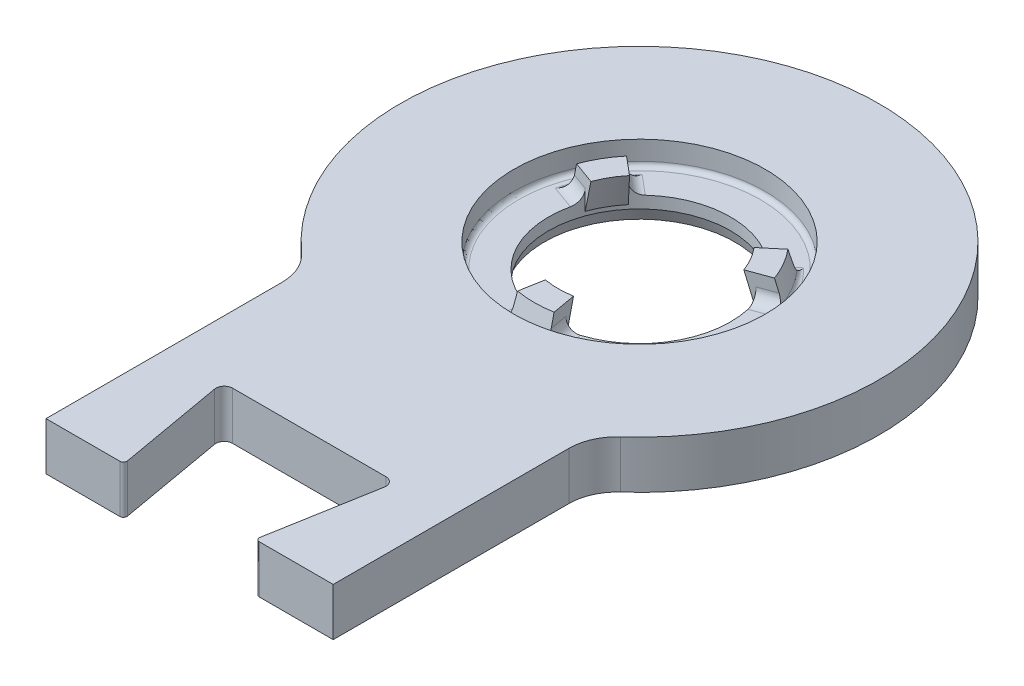
SolidWorks part; units mm, degrees
ref_plane "Front Plane" through (0, 0, 0) normal (0, 0, 1) x (1, 0, 0)
ref_plane "Top Plane" through (0, 0, 0) normal (0, 1, 0) x (1, 0, 0)
ref_plane "Right Plane" through (0, 0, 0) normal (1, 0, 0) x (0, 0, -1)
sketch "Sketch1" plane through (0, 0, 0) normal (0, 1, 0) x (1, 0, 0)
  line L0 (-6, 6) -> (-6, -13.2915)
  line L1 (-6, -19) -> (-2.7023, -19)
  line L2 (6, -19) -> (6, -13.2915)
  line L3 (6, 6) -> (-6, 6)
  line L4 (-6, -13.2915) -> (-6, -19)
  line L5 (6, -13.2915) -> (6, 6)
  line L6 (0, -19) -> (0, 0) construction
  line L7 (-2.6007, -19) -> (-3.5, -13.9) construction
  line L8 (-3.5, -13.9) -> (0, -13.9) construction
  line L9 (-2.7023, -19) -> (-3.6192, -13.8)
  line L10 (-3.6192, -13.8) -> (0, -13.8)
  line L11 (-2.6992, -19.0174) -> (-3.6192, -13.8) construction
  line L12 (2.7023, -19) -> (6, -19)
  line L13 (3.6192, -13.8) -> (0, -13.8)
  line L14 (2.7023, -19) -> (3.6192, -13.8)
  circle A0 centre (0, 0) radius 4
  dimension "D1" = 8
  dimension "D5" = 6
  dimension "D7" = 80
  dimension "D2" = 25
  dimension "D3" = 6
  dimension "D4" = 12
  dimension "D8" = 3.5
  dimension "D9" = 5.1
  dimension "D10" = 0.1
extrude "Boss-Extrude1" add sketch "Sketch1" along normal blind 2
sketch "Sketch2" plane through (0, 0, 0) normal (0, 1, 0) x (1, 0, 0)
  circle A0 centre (0, 0) radius 10
  circle A1 centre (0, 0) radius 3.8
  dimension "D1" = 20
  dimension "D2" = 7.6
extrude "Boss-Extrude2" add sketch "Sketch2" along normal blind 2
sketch "Sketch3" plane through (0, 0, 0) normal (0, -1, 0) x (1, 0, 0)
  line L0 (-3, 0) -> (-3, 4)
  line L1 (3, 0) -> (3, 4)
  arc A0 (-3, 0) -> (3, 0) centre (0, 0) ccw
  arc A1 (-3, 4) -> (3, 4) centre (0, 0) ccw
extrude "Boss-Extrude3" [suppressed] add sketch "Sketch3" along normal blind 4
fillet "Fillet1" [suppressed] radius 0.5
fillet "Fillet2" [suppressed] radius 1
sketch "Sketch4" plane through (0, 2, 0) normal (0, 1, 0) x (1, 0, 0)
  line L0 (-6, -8) -> (-6, -19) construction
  line L1 (-6, -18.8) -> (6, -18.8)
  line L2 (-6, -18.8) -> (-6, -19)
  line L3 (-6, -19) -> (6, -19)
  line L4 (6, -18.8) -> (6, -19)
  dimension "D1" = 0.2
extrude "Cut-Extrude1" cut sketch "Sketch4" against normal blind 4
fillet "Fillet3" radius 0.35 2 edges at (3.6192, 1, 13.8) (-3.6192, 1, 13.8)
fillet "Fillet4" radius 0.15 2 edges at (2.7375, 1, 18.8) (-2.7375, 1, 18.8)
sketch "Sketch5" plane through (0, 0, 0) normal (0, 1, 0) x (1, 0, 0)
  circle A1 centre (0, 0) radius 3
  circle A2 centre (0, 0) radius 2.1
  dimension "D1" = 4.2
  dimension "D2" = 6
extrude "Boss-Extrude4" [suppressed] add sketch "Sketch5" along normal blind 13
fillet "Fillet5" [suppressed] radius 2
fillet "Fillet6" radius 2 2 edges at (-6, 1, 8) (6, 1, 8)
sketch "Sketch6" plane through (0, 2, 0) normal (0, 1, 0) x (1, 0, 0)
  circle A0 centre (0, 0) radius 3.5
  dimension "D1" = 7
extrude "Boss-Extrude5" [suppressed] add sketch "Sketch6" along normal blind 2 contours A0
sketch "Sketch7" [suppressed] plane through (0, 4, 0) normal (0, 1, 0) x (1, 0, 0)
  circle A0 centre (0, 0) radius 3.15
extrude "Cut-Extrude3" [suppressed] cut sketch "Sketch7" against normal blind 3.2
fillet "Fillet7" [suppressed] radius 2
fillet "Fillet8" [suppressed] radius 1
fillet "Fillet9" [suppressed] radius 0.1
sketch "Sketch8" plane through (0, 2, 0) normal (0, 1, 0) x (1, 0, 0)
  line L0 (0, 0) -> (0, 3.9) construction
  line L1 (-0.5, 3.65) -> (0, 2.65)
  line L2 (-0.5, 4.15) -> (0.5, 4.15)
  line L3 (-0.5, 4.15) -> (-0.5, 3.65)
  line L4 (-0.5, 3.65) -> (0.5, 3.65) construction
  line L5 (0.5, 4.15) -> (0.5, 3.65)
  line L6 (-0.5, 4.15) -> (0.5, 3.65) construction
  line L7 (-0.5, 3.65) -> (0.5, 4.15) construction
  line L8 (0, 2.65) -> (0.5, 3.65)
  dimension "D1" = 3.9
  dimension "D2" = 0.5
  dimension "D3" = 1
  dimension "D4" = 1
extrude "Boss-Extrude6" [suppressed] add sketch "Sketch8" against normal blind 2
pattern_circular "CirPattern1" [suppressed] count 5 over 360
sketch "Sketch11" plane through (0, 2, 0) normal (0, 1, 0) x (1, 0, 0)
  circle A0 centre (0, 0) radius 4
  circle A1 centre (0, 0) radius 5
  dimension "D1" = 8
  dimension "D2" = 10
extrude "Boss-Extrude7" [suppressed] add sketch "Sketch11" along normal blind 2 draft 3
sketch "Sketch13" plane through (0, 2, 0) normal (0, 1, 0) x (1, 0, 0)
  circle A0 centre (0, 0) radius 5 construction
  circle A1 centre (0, 0) radius 5.25
  dimension "D1" = 10
  dimension "D2" = 10.5
extrude "Cut-Extrude5" cut sketch "Sketch13" against normal blind 1
fillet "Fillet10" [suppressed] radius 0.2
sketch "Sketch12" plane through (0, 0, 0) normal (1, 0, 0) x (0, 0, -1)
  line L0 (0, 0) -> (-4, 0) construction
  line L1 (-7.4536, 0) -> (10, 0) construction
  line L2 (-3.8, 0) -> (3.8, 0) construction
  line L3 (0, 0) -> (0, 2) construction
  line L4 (3.8, 2) -> (-3.8, 2) construction
  line L5 (-4, 0) -> (-3.4, 2)
  line L6 (-3.4, 2) -> (-4.4, 2)
  line L7 (-4.4, 2) -> (-5, 0)
  line L8 (-5, 0) -> (-4, 0)
  line L9 (-4, 0) -> (-4.0344, -0.0135)
  dimension "D1" = 0
  dimension "D2" = 3.4
  dimension "D3" = 1
  dimension "D4" = 4
revolve "Revolve2" add sketch "Sketch12" angle 20 mid plane about L3
pattern_circular "CirPattern2" count 3 over 360 about axis through (0, 0, 0) along (0, 1, 0) of "Revolve2"
chamfer "Chamfer1" distance 0.5 angle 20 1 edges at (0, 0, 3.8)
fillet "Fillet13" radius 0.5 6 edges at (-3.9937, 1, -1.4536) (-3.2557, 1, -2.7318) (3.2557, 1, -2.7318) (3.9937, 1, -1.4536) (0.738, 1, 4.1854) (-0.738, 1, 4.1854)
fillet "Fillet14" radius 0.2 4 edges at (0, 1, 5.25) (-4.0703, 1, -2.35) (4.0703, 1, -2.35) (0, 1, 4.7)
